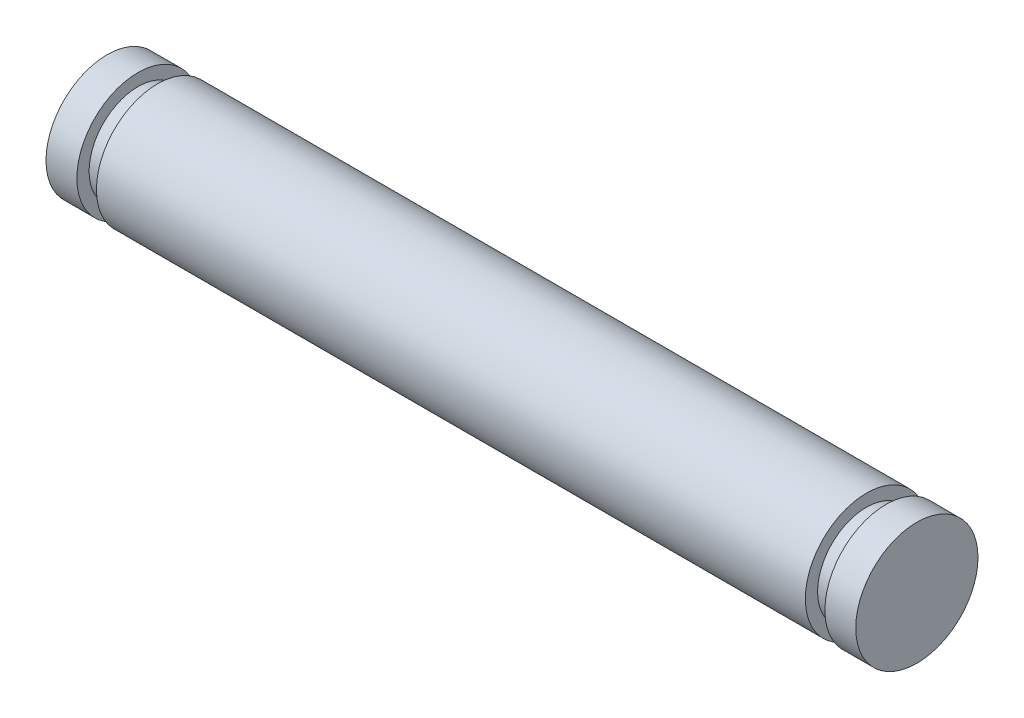
SolidWorks part; units mm, degrees
material "Plain Carbon Steel"
ref_plane "Front Plane" through (0, 0, 0) normal (0, 0, 1) x (1, 0, 0)
ref_plane "Top Plane" through (0, 0, 0) normal (0, 1, 0) x (1, 0, 0)
ref_plane "Right Plane" through (0, 0, 0) normal (1, 0, 0) x (0, 0, -1)
sketch "Sketch1" plane through (0, 0, 0) normal (1, 0, 0) x (0, 0, -1)
  circle A0 centre (0, 0) radius 2
  dimension "D1" = 4
extrude "Boss-Extrude1" add sketch "Sketch1" along normal mid plane 26.5
ref_axis "Axis1" through (-14.575, 0, 0) along (1, 0, 0)
sketch "Sketch2" plane through (0, 0, 0) normal (0, 1, 0) x (1, 0, 0)
  line L0 (-14.575, 0) -> (14.575, 0) construction
  line L1 (-12.24, 2) -> (-11.6, 2)
  line L2 (-12.24, 2) -> (-12.24, 1.6)
  line L3 (-12.24, 1.6) -> (-11.6, 1.6)
  line L4 (-11.6, 2) -> (-11.6, 1.6)
  line L5 (13.25, 2) -> (-13.25, 2) construction
  dimension "D1" = 0.64
  dimension "D2" = 1.6
  dimension "D3" = 11.6
revolve "Cut-Revolve1" cut sketch "Sketch2" angle 360 about axis through (-14.575, 0, 0) along (1, 0, 0)
mirror "Mirror1" about plane through (0, 0, 0) normal (1, 0, 0) of "Cut-Revolve1"
